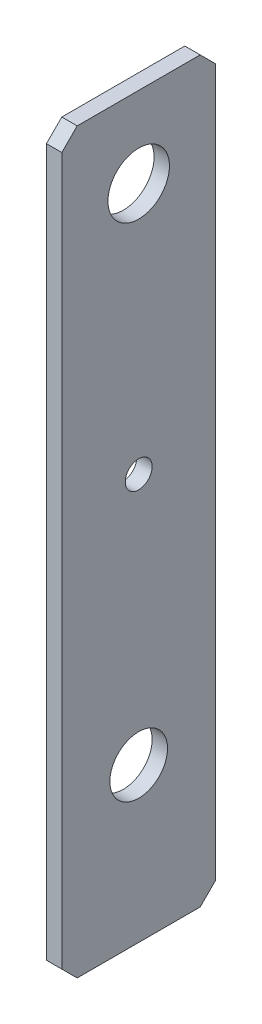
SolidWorks part; units mm, degrees
ref_plane "Front Plane" through (0, 0, 0) normal (0, 0, 1) x (1, 0, 0)
ref_plane "Top Plane" through (0, 0, 0) normal (0, 1, 0) x (1, 0, 0)
ref_plane "Right Plane" through (0, 0, 0) normal (1, 0, 0) x (0, 0, -1)
sketch "Sketch1" plane through (0, 0, 0) normal (1, 0, 0) x (0, 0, -1)
  line L1 (0, 0) -> (20, 0)
  line L2 (0, 0) -> (0, 96)
  line L3 (0, 96) -> (20, 96)
  line L4 (20, 0) -> (20, 96)
  dimension "D1" = 20
  dimension "D2" = 96
extrude "Boss-Extrude1" add sketch "Sketch1" along normal blind 2
sketch "Sketch2" plane through (2, 0, 0) normal (1, 0, 0) x (0, 0, -1)
  line L0 (10, 96) -> (10, 0) construction
  line L1 (20, 96) -> (0, 96) construction
  line L2 (0, 0) -> (20, 0) construction
  circle A0 centre (10, 85.5) radius 4
  circle A1 centre (10, 52.75) radius 1.75
  circle A2 centre (10, 20) radius 3.75
  dimension "D1" = 7.5
  dimension "D2" = 3.5
  dimension "D3" = 8
  dimension "D5" = 32.75
  dimension "D4" = 20
  dimension "D6" = 10.5
extrude "Cut-Extrude1" cut sketch "Sketch2" against normal through all
chamfer "Chamfer1" distance 2 angle 45 4 edges at (1, 0, -20) (1, 0, 0) (1, 96, -20) (1, 96, 0)
